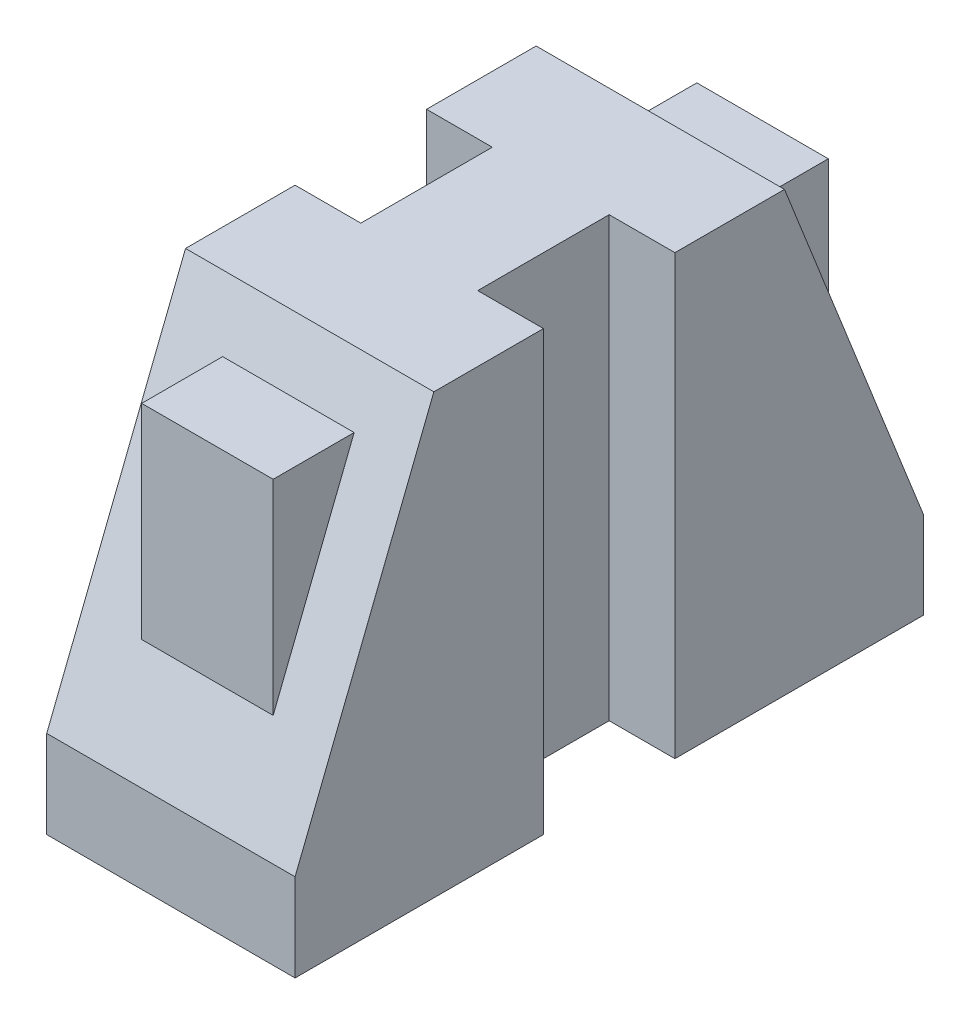
SolidWorks part; units mm, degrees
ref_plane "Alzado" through (0, 0, 0) normal (0, 0, 1) x (1, 0, 0)
ref_plane "Planta" through (0, 0, 0) normal (0, 1, 0) x (1, 0, 0)
ref_plane "Vista lateral" through (0, 0, 0) normal (1, 0, 0) x (0, 0, -1)
sketch "Croquis1" plane through (0, 0, 0) normal (1, 0, 0) x (0, 0, -1)
  line L0 (0, 51.6462) -> (0, -51.6462) construction
  line L1 (43, -12) -> (-43, -12)
  line L2 (-43, -12) -> (-43, 0)
  line L3 (-43, 0) -> (-24, 48)
  line L4 (-24, 48) -> (24, 48)
  line L5 (43, -12) -> (43, 0)
  line L6 (43, 0) -> (24, 48)
  point P2 (0, 30.0517)
  point P3 (0, 0)
  point P9 (0, 51.6462)
  point P12 (0, -12)
  point P13 (0, 48)
  point P14 (0, 0)
  point P15 (22.5588, 48)
  dimension "D1" = 86
  dimension "D2" = 60
  dimension "D3" = 12
  dimension "D4" = 48
extrude "Saliente-Extruir2" add sketch "Croquis1" against normal mid plane 34
sketch "Croquis3" plane through (0, 48, 0) normal (0, 1, 0) x (1, 0, 0)
  line L0 (-17, 24) -> (-17, -24) construction
  line L1 (-17, 9) -> (-8, 9)
  line L2 (-17, 9) -> (-17, -9)
  line L3 (-17, -9) -> (-8, -9)
  line L4 (-8, 9) -> (-8, -9)
  line L5 (0, 24) -> (0, -24) construction
  line L6 (-17, 24) -> (17, 24) construction
  line L7 (-17, -24) -> (17, -24) construction
  line L8 (-17, 0) -> (17, 0) construction
  line L9 (17, 24) -> (17, -24) construction
  line L10 (17, -9) -> (8, -9)
  line L11 (8, 9) -> (8, -9)
  line L12 (17, 9) -> (8, 9)
  line L13 (17, 9) -> (17, -9)
  point P12 (-17, 0)
  point P18 (0, 0)
  dimension "D1" = 15
  dimension "D2" = 16
extrude "Cortar-Extruir2" cut sketch "Croquis3" against normal through all
sketch "Croquis4" plane through (0, 0, 0) normal (1, 0, 0) x (0, 0, -1)
  line L0 (-38, 12.6316) -> (-38, 40.6316)
  line L1 (-24, 48) -> (-43, 0) construction
  line L2 (-38, 40.6316) -> (-26.9167, 40.6316)
  line L3 (0, 53.0008) -> (0, -18.6916) construction
  line L5 (38, 12.6316) -> (38, 40.6316)
  line L6 (38, 40.6316) -> (26.9167, 40.6316)
  line L7 (-38, 12.6316) -> (-26.9167, 40.6316)
  line L8 (38, 12.6316) -> (26.9167, 40.6316)
  dimension "D1" = 28
  dimension "D2" = 76
extrude "Saliente-Extruir4" add sketch "Croquis4" along normal mid plane 18
